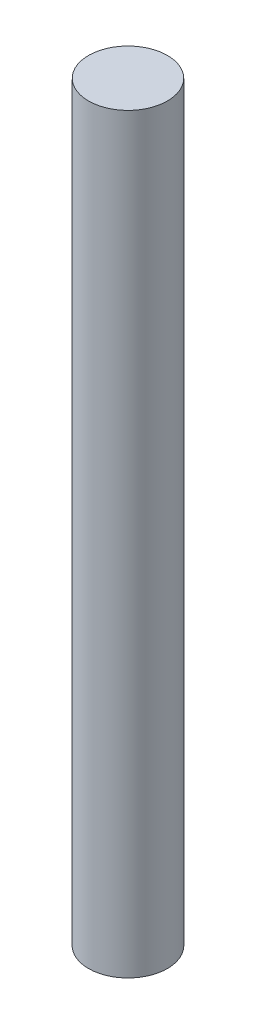
SolidWorks part; units mm, degrees
ref_plane "Front Plane" through (0, 0, 0) normal (0, 0, 1) x (1, 0, 0)
ref_plane "Top Plane" through (0, 0, 0) normal (0, 1, 0) x (1, 0, 0)
ref_plane "Right Plane" through (0, 0, 0) normal (1, 0, 0) x (0, 0, -1)
sketch "Sketch1" plane through (0, 0, 0) normal (0, 1, 0) x (1, 0, 0)
  circle A0 centre (0, 0) radius 1.05
  dimension "D1" = 2.1
extrude "Boss-Extrude1" add sketch "Sketch1" along normal blind 20
